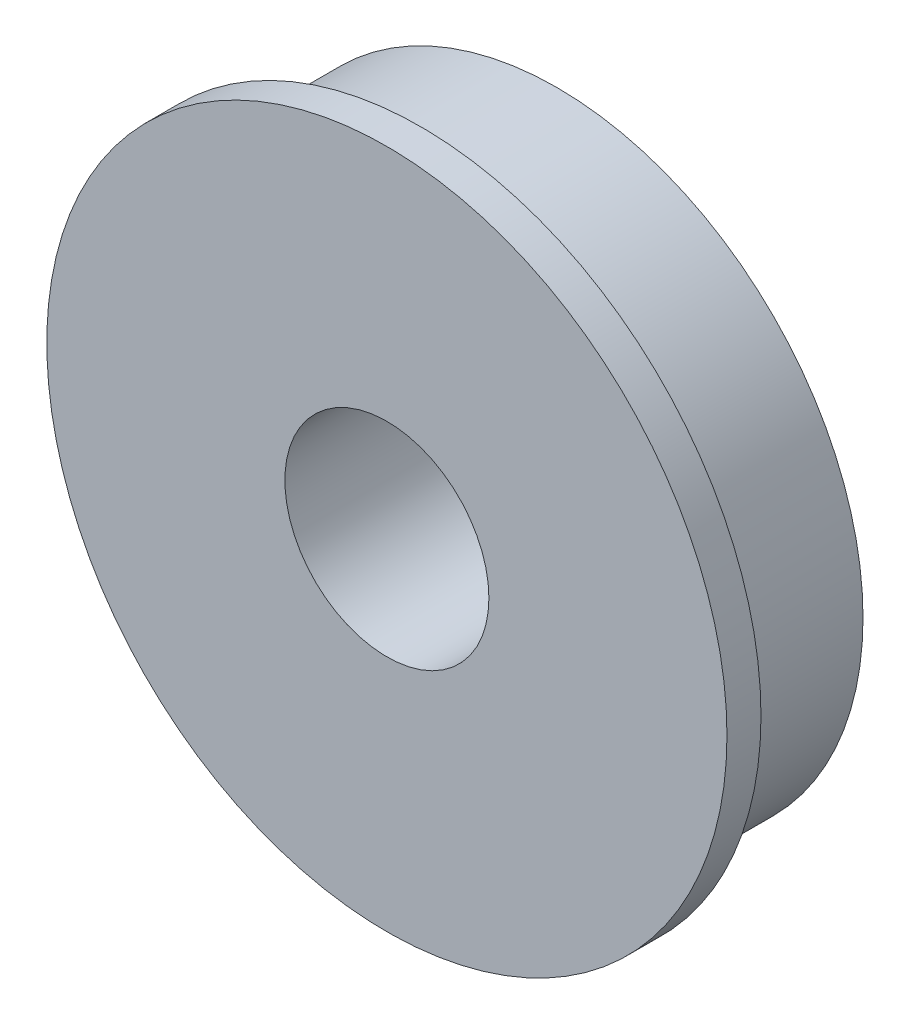
SolidWorks part; units mm, degrees
ref_plane "Front Plane" through (0, 0, 0) normal (0, 0, 1) x (1, 0, 0)
ref_plane "Top Plane" through (0, 0, 0) normal (0, 1, 0) x (1, 0, 0)
ref_plane "Right Plane" through (0, 0, 0) normal (1, 0, 0) x (0, 0, -1)
sketch "Sketch1" plane through (0, 0, 0) normal (1, 0, 0) x (0, 0, -1)
  line L0 (0, 4.7625) -> (7.9375, 4.7625)
  line L1 (7.9375, 4.7625) -> (7.9375, 14.2875)
  line L2 (7.9375, 14.2875) -> (1.5875, 14.2875)
  line L3 (1.5875, 14.2875) -> (1.5875, 15.875)
  line L4 (1.5875, 15.875) -> (0, 15.875)
  line L5 (0, 15.875) -> (0, 4.7625)
  line L6 (0, 0) -> (15.4669, 0) construction
  dimension "D1" = 4.7625
  dimension "D2" = 14.2875
  dimension "D3" = 1.5875
  dimension "D4" = 6.35
revolve "Revolve1" add sketch "Sketch1" angle 360 about L6
